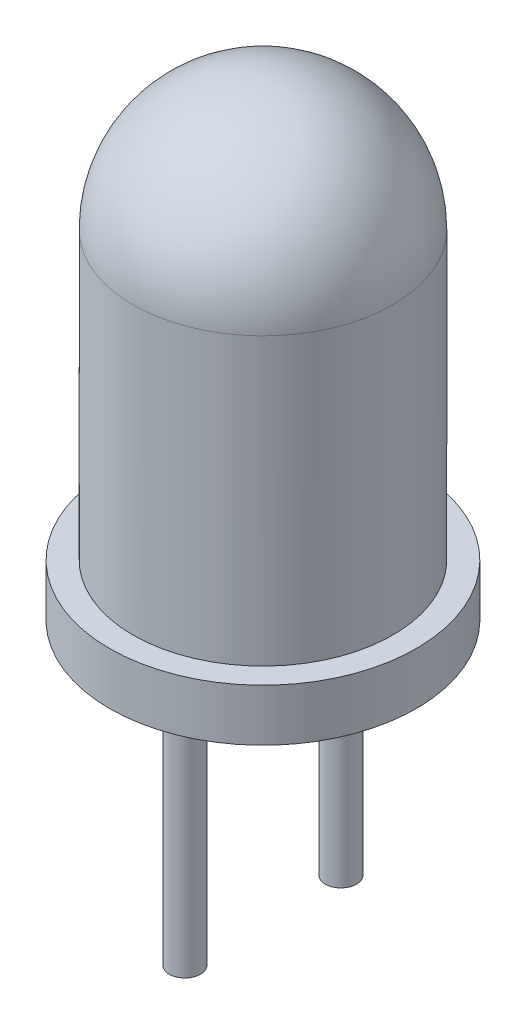
SolidWorks part; units mm, degrees
ref_plane "Front Plane" through (0, 0, 0) normal (0, 0, 1) x (1, 0, 0)
ref_plane "Top Plane" through (0, 0, 0) normal (0, 1, 0) x (1, 0, 0)
ref_plane "Right Plane" through (0, 0, 0) normal (1, 0, 0) x (0, 0, -1)
sketch "Sketch1" plane through (0, 0, 0) normal (0, 1, 0) x (1, 0, 0)
  circle A0 centre (0, 0) radius 2.95
  dimension "D1" = 5.9
extrude "Boss-Extrude1" add sketch "Sketch1" along normal blind 1
sketch "Sketch3" plane through (0, 0, 0) normal (0, 0, 1) x (1, 0, 0)
  line L0 (2.95, 1) -> (-2.95, 1) construction
  line L1 (0, 1) -> (2.5, 1)
  line L2 (0, 1) -> (0, 6.5)
  line L4 (2.5, 1) -> (2.5, 6.5)
  line L5 (0, 6.5) -> (0, 9)
  arc A0 (2.5, 6.5) -> (0, 9) centre (0, 6.5) ccw
  dimension "D1" = 2.5
  dimension "D2" = 8
revolve "Revolve1" add sketch "Sketch3" angle 360 about L2
sketch "Sketch5" plane through (0, 0, 0) normal (0, -1, 0) x (1, 0, 0)
  circle A0 centre (0, 1.5) radius 0.3
  dimension "D1" = 0.6
  dimension "D2" = 1.5
extrude "Boss-Extrude2" add sketch "Sketch5" along normal blind 5
mirror "Mirror1" about plane through (0, 0, 0) normal (0, 0, 1) of "Boss-Extrude2"
